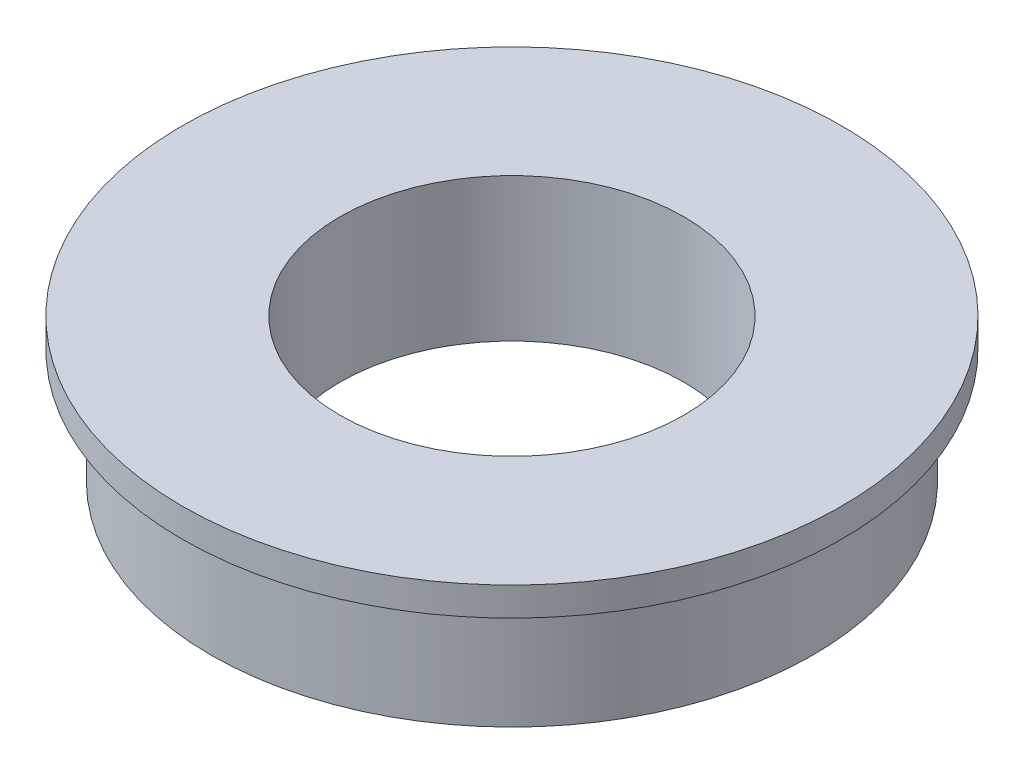
SolidWorks part; units mm, degrees
ref_plane "前视基准面" through (0, 0, 0) normal (0, 0, 1) x (1, 0, 0)
ref_plane "上视基准面" through (0, 0, 0) normal (0, 1, 0) x (1, 0, 0)
ref_plane "右视基准面" through (0, 0, 0) normal (1, 0, 0) x (0, 0, -1)
sketch "Sketch1" plane through (0, 0, 0) normal (1, 0, 0) x (0, 0, -1)
  line L1 (11.5, -1.0677) -> (11.5, -2.0677)
  line L2 (11.5, -2.0677) -> (10.5, -2.0677)
  line L3 (10.5, -2.0677) -> (10.5, -6.0677)
  line L4 (10.5, -6.0677) -> (6, -6.0677)
  line L5 (6, -6.0677) -> (6, -1.0677)
  line L7 (11.5, -1.0677) -> (6, -1.0677)
  line L8 (0, 4.0059) -> (0, -9.514) construction
  dimension "D1" = 10.5
  dimension "D2" = 6
  dimension "D3" = 11.5
  dimension "D4" = 4
  dimension "D5" = 1
revolve "Revolve1" add sketch "Sketch1" angle 360 about L8
